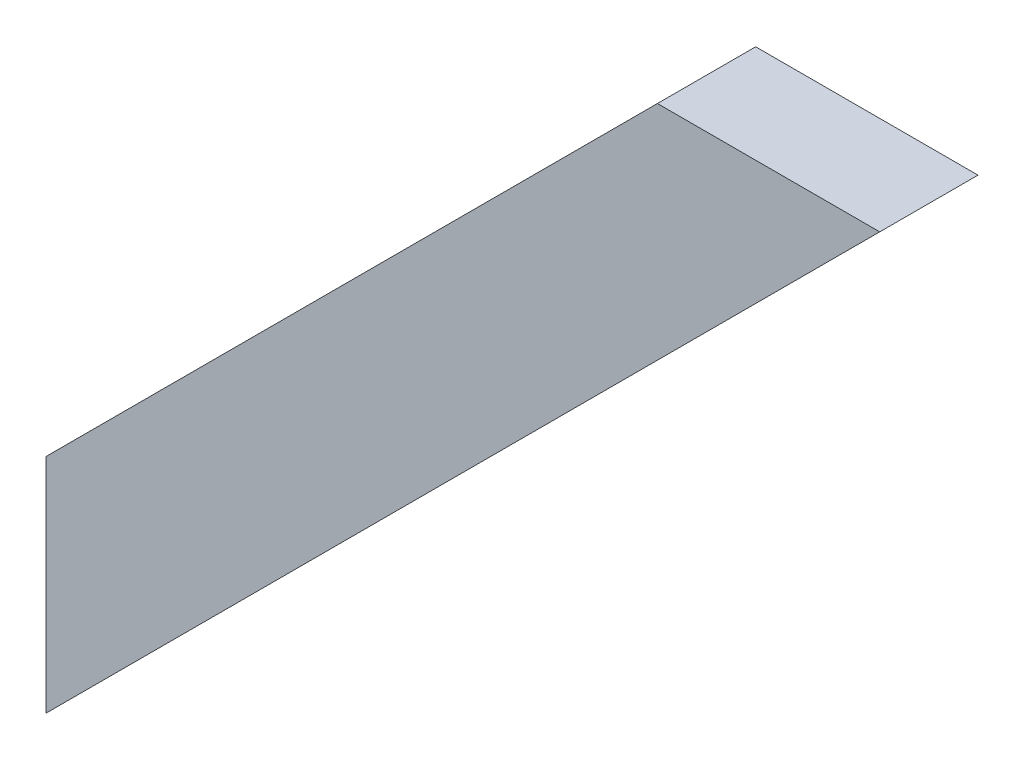
SolidWorks part; units mm, degrees
ref_plane "Plan de face" through (0, 0, 0) normal (0, 0, 1) x (1, 0, 0)
ref_plane "Plan de dessus" through (0, 0, 0) normal (0, 1, 0) x (1, 0, 0)
ref_plane "Plan de droite" through (0, 0, 0) normal (1, 0, 0) x (0, 0, -1)
sketch "Esquisse1" plane through (0, 0, 0) normal (0, 0, 1) x (1, 0, 0)
  line L0 (0, 0) -> (212.132, 212.132)
  line L1 (212.132, 212.132) -> (155.5635, 212.132)
  line L2 (155.5635, 212.132) -> (0, 56.5685)
  line L3 (0, 56.5685) -> (0, 0)
  dimension "D1" = 40
  dimension "D2" = 45
  dimension "D3" = 300
extrude "Boss.-Extru.1" add sketch "Esquisse1" along normal blind 25
